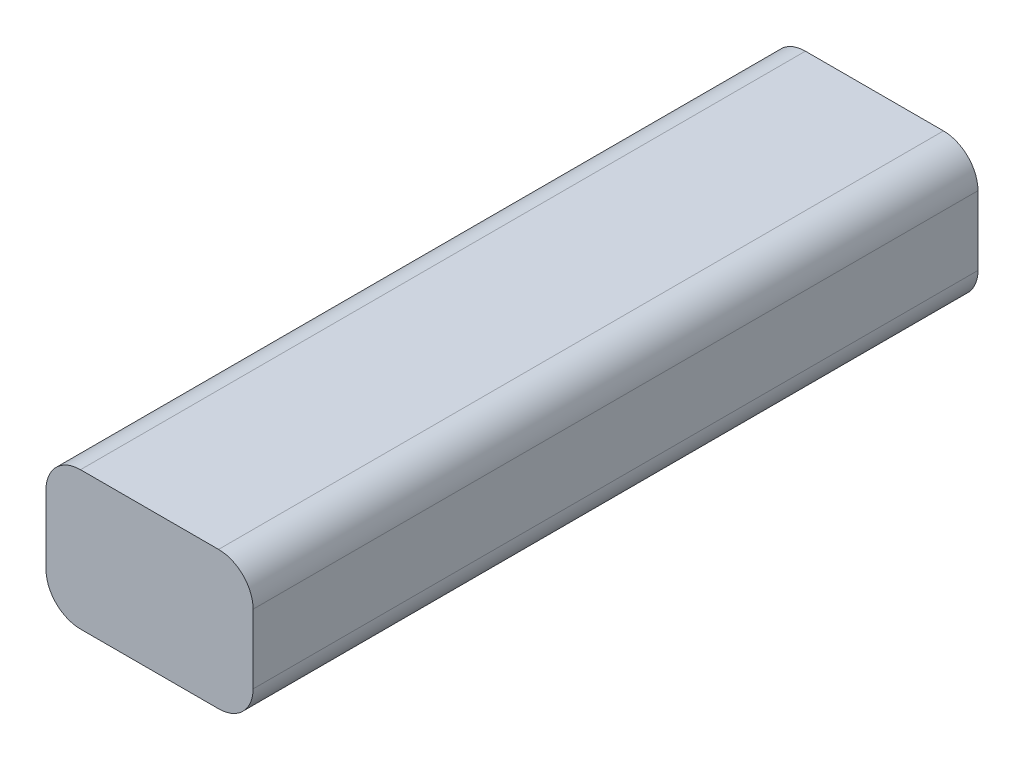
SolidWorks part; units mm, degrees
ref_plane "Front Plane" through (0, 0, 0) normal (0, 0, 1) x (1, 0, 0)
ref_plane "Top Plane" through (0, 0, 0) normal (0, 1, 0) x (1, 0, 0)
ref_plane "Right Plane" through (0, 0, 0) normal (1, 0, 0) x (0, 0, -1)
sketch "Sketch1" plane through (0, 0, 0) normal (0, 1, 0) x (1, 0, 0)
  line L1 (650.4487, 615.7499) -> (620.4487, 615.7499)
  line L2 (650.4487, 615.7499) -> (650.4487, 720.7499)
  line L3 (650.4487, 720.7499) -> (620.4487, 720.7499)
  line L4 (620.4487, 615.7499) -> (620.4487, 720.7499)
  dimension "D1" = 30
  dimension "D2" = 105
extrude "Boss-Extrude1" add sketch "Sketch1" along normal blind 20
fillet "Fillet1" radius 5 4 edges at (620.4487, 0, -668.2499) (650.4487, 0, -668.2499) (620.4487, 20, -668.2499) (650.4487, 20, -668.2499)
